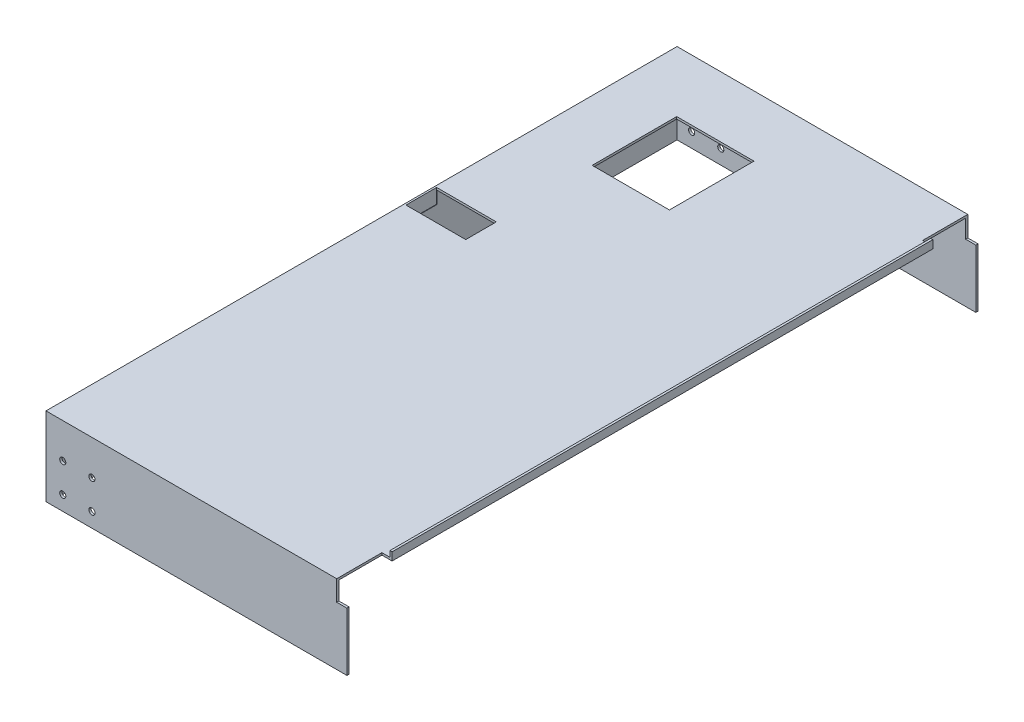
SolidWorks part; units mm, degrees
ref_plane "Front Plane" through (0, 0, 0) normal (0, 0, 1) x (1, 0, 0)
ref_plane "Top Plane" through (0, 0, 0) normal (0, 1, 0) x (1, 0, 0)
ref_plane "Right Plane" through (0, 0, 0) normal (1, 0, 0) x (0, 0, -1)
sketch "Sketch4" plane through (0, 0, 0) normal (0, 1, 0) x (1, 0, 0)
  line L0 (124.0135, 430) -> (329.0135, 430)
  line L1 (329.0135, 430) -> (329.0135, 0)
  line L2 (329.0135, 0) -> (124.0135, 0)
  line L3 (124.0135, 0) -> (124.0135, 200)
  line L7 (124.0135, 365) -> (124.0135, 430)
  line L8 (124.0135, 200) -> (124.0135, 365)
  line L9 (329.0135, 80.0946) -> (329.0135, 106.0946) construction
  dimension "D2" = 65
  dimension "D4" = 200
  dimension "D5" = 205
  dimension "D6" = 205
extrude "Boss-Extrude4" add sketch "Sketch4" along normal blind 1.5 separate body
sketch "Sketch5" plane through (0, 0, 0) normal (0, 0, 1) x (1, 0, 0)
  line L1 (124.0135, 1.5) -> (329.0135, 1.5)
  line L2 (124.0135, 1.5) -> (124.0135, -52.5)
  line L3 (124.0135, -52.5) -> (329.0135, -52.5)
  line L4 (329.0135, 1.5) -> (329.0135, -52.5)
  dimension "D1" = 54
sketch "Sketch7" plane through (0, 0, -430) normal (0, 0, -1) x (-1, 0, 0)
  line L1 (-124.0135, 1.5) -> (-329.0135, 1.5)
  line L2 (-124.0135, 1.5) -> (-124.0135, -52.5)
  line L3 (-124.0135, -52.5) -> (-329.0135, -52.5)
  line L4 (-329.0135, 1.5) -> (-329.0135, -52.5)
  dimension "D1" = 54
  dimension "D2" = 205
sketch "Sketch8" plane through (0, 1.5, 0) normal (0, 1, 0) x (1, 0, 0)
  line L0 (124.0135, 430) -> (329.0135, 430) construction
  line L1 (329.0135, 0) -> (327.5135, 0)
  line L2 (329.0135, 0) -> (329.0135, 430)
  line L3 (329.0135, 430) -> (327.5135, 430)
  line L4 (327.5135, 0) -> (327.5135, 430)
  dimension "D1" = 1.5
extrude "Boss-Extrude5" add sketch "Sketch5" along normal blind 1.5
extrude "Boss-Extrude14" add sketch "Sketch8" along normal blind 4
extrude "Boss-Extrude18" add sketch "Sketch7" along normal blind 1.5
sketch "Sketch9" plane through (124.0135, 0, 0) normal (-1, 0, 0) x (0, 0, 1)
  line L1 (-431.5, 1.5) -> (1.5, 1.5)
  line L2 (-431.5, 1.5) -> (-431.5, -52.5)
  line L3 (-431.5, -52.5) -> (1.5, -52.5)
  line L4 (1.5, 1.5) -> (1.5, -52.5)
extrude "Boss-Extrude19" add sketch "Sketch9" along normal blind 1.5
sketch "Sketch10" plane through (0, 0, -431.5) normal (0, 0, -1) x (-1, 0, 0)
  circle A0 centre (-154.0135, -42.5) radius 2.1
sketch "Sketch11" plane through (0, 0, -431.5) normal (0, 0, -1) x (-1, 0, 0)
  circle A0 centre (-134.0237, -42.5218) radius 2.1
sketch "Sketch12" plane through (0, 0, -431.5) normal (0, 0, -1) x (-1, 0, 0)
  circle A0 centre (-134.0173, -22.4773) radius 2.1
sketch "Sketch13" plane through (0, 0, -431.5) normal (0, 0, -1) x (-1, 0, 0)
  circle A0 centre (-154.0032, -22.5144) radius 2.1
sketch "Sketch14" plane through (0, 0, 1.5) normal (0, 0, 1) x (1, 0, 0)
  circle A0 centre (134.0173, -22.4773) radius 2.1
sketch "Sketch15" plane through (0, 0, 1.5) normal (0, 0, 1) x (1, 0, 0)
  circle A0 centre (154.0032, -22.5144) radius 2.1
sketch "Sketch16" plane through (0, 0, 1.5) normal (0, 0, 1) x (1, 0, 0)
  circle A0 centre (134.0237, -42.5218) radius 2.1
sketch "Sketch17" plane through (0, 0, 1.5) normal (0, 0, 1) x (1, 0, 0)
  circle A0 centre (154.0135, -42.5) radius 2.1
extrude "Cut-Extrude1" cut sketch "Sketch10" against normal blind 10
extrude "Cut-Extrude2" cut sketch "Sketch17" against normal blind 10
extrude "Cut-Extrude3" cut sketch "Sketch16" against normal blind 10
extrude "Cut-Extrude4" cut sketch "Sketch11" against normal blind 10
extrude "Cut-Extrude5" cut sketch "Sketch12" against normal blind 10
extrude "Cut-Extrude6" cut sketch "Sketch13" against normal blind 10
extrude "Cut-Extrude7" cut sketch "Sketch14" against normal blind 10
extrude "Cut-Extrude8" cut sketch "Sketch15" against normal blind 10
sketch "Sketch18" plane through (0, 1.5, 0) normal (0, 1, 0) x (1, 0, 0)
  line L1 (123.7353, 265.2813) -> (164.7353, 265.2813)
  line L2 (123.7353, 265.2813) -> (123.7353, 244.2776)
  line L3 (123.7353, 244.2776) -> (164.7353, 244.2776)
  line L4 (164.7353, 265.2813) -> (164.7353, 244.2776)
  dimension "D1" = 41
extrude "Cut-Extrude9" cut sketch "Sketch18" against normal blind 10
sketch "Sketch21" plane through (0, 1.5, 0) normal (0, 1, 0) x (1, 0, 0)
  line L1 (164.0135, 389.7654) -> (217.0135, 389.7654)
  line L2 (164.0135, 389.7654) -> (164.0135, 331.7654)
  line L3 (164.0135, 331.7654) -> (217.0135, 331.7654)
  line L4 (217.0135, 389.7654) -> (217.0135, 331.7654)
extrude "Cut-Extrude12" cut sketch "Sketch21" against normal blind 10
sketch "Sketch23" plane through (0, 0, 1.5) normal (0, 0, 1) x (1, 0, 0)
  line L0 (329.0135, -52.5) -> (329.0135, 1.5) construction
  line L1 (322.0135, 5.5) -> (329.0135, 5.5)
  line L2 (322.0135, 5.5) -> (322.0135, -12.5)
  line L3 (322.0135, -12.5) -> (329.0135, -12.5)
  line L4 (329.0135, 5.5) -> (329.0135, -12.5)
extrude "Cut-Extrude14" cut sketch "Sketch23" against normal blind 31
sketch "Sketch24" plane through (0, 0, -431.5) normal (0, 0, -1) x (-1, 0, 0)
  line L1 (-329.0135, 5.5) -> (-322.0135, 5.5)
  line L2 (-329.0135, 5.5) -> (-329.0135, -12.5)
  line L3 (-329.0135, -12.5) -> (-322.0135, -12.5)
  line L4 (-322.0135, 5.5) -> (-322.0135, -12.5)
extrude "Cut-Extrude15" cut sketch "Sketch24" against normal blind 31
